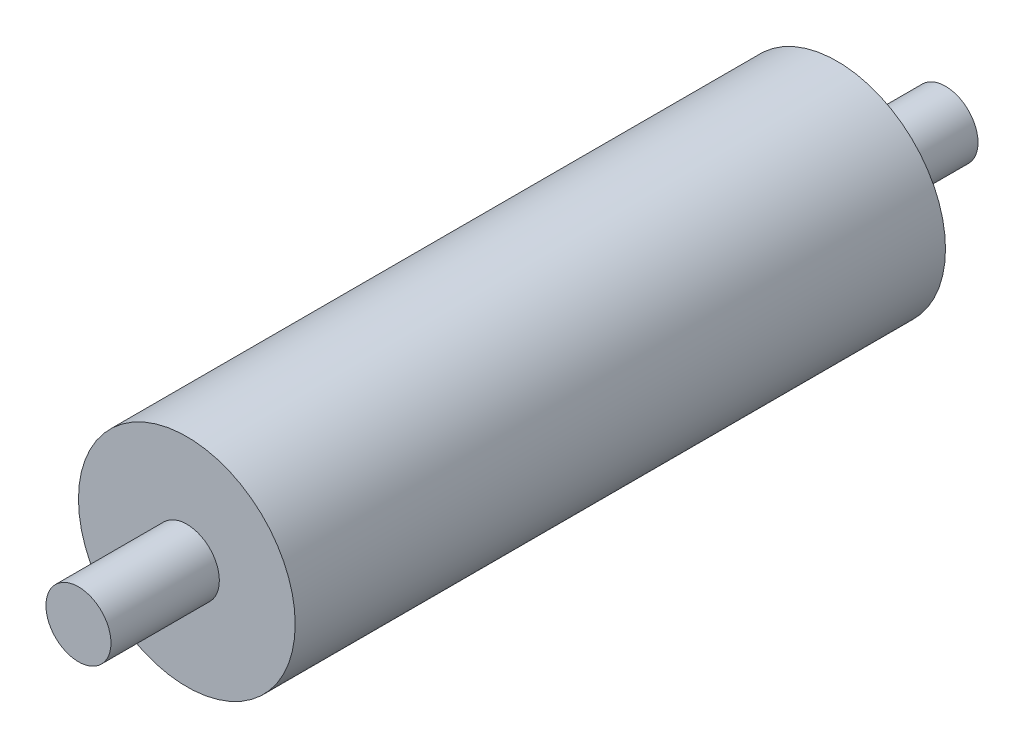
SolidWorks part; units mm, degrees
ref_plane "Front Plane" through (0, 0, 0) normal (0, 0, 1) x (1, 0, 0)
ref_plane "Top Plane" through (0, 0, 0) normal (0, 1, 0) x (1, 0, 0)
ref_plane "Right Plane" through (0, 0, 0) normal (1, 0, 0) x (0, 0, -1)
sketch "Sketch1" plane through (0, 0, 0) normal (0, 0, 1) x (1, 0, 0)
  circle A0 centre (0, 0) radius 50
  dimension "D1" = 100
extrude "Boss-Extrude1" add sketch "Sketch1" along normal blind 300
sketch "Sketch2" plane through (0, 0, 300) normal (0, 0, 1) x (1, 0, 0)
  circle A0 centre (0, 0) radius 15
  dimension "D1" = 30
extrude "Boss-Extrude2" add sketch "Sketch2" along normal blind 50
pattern_linear "LPattern1" count 2 spacing 350 along (0, 0, -1) of "Boss-Extrude2"
